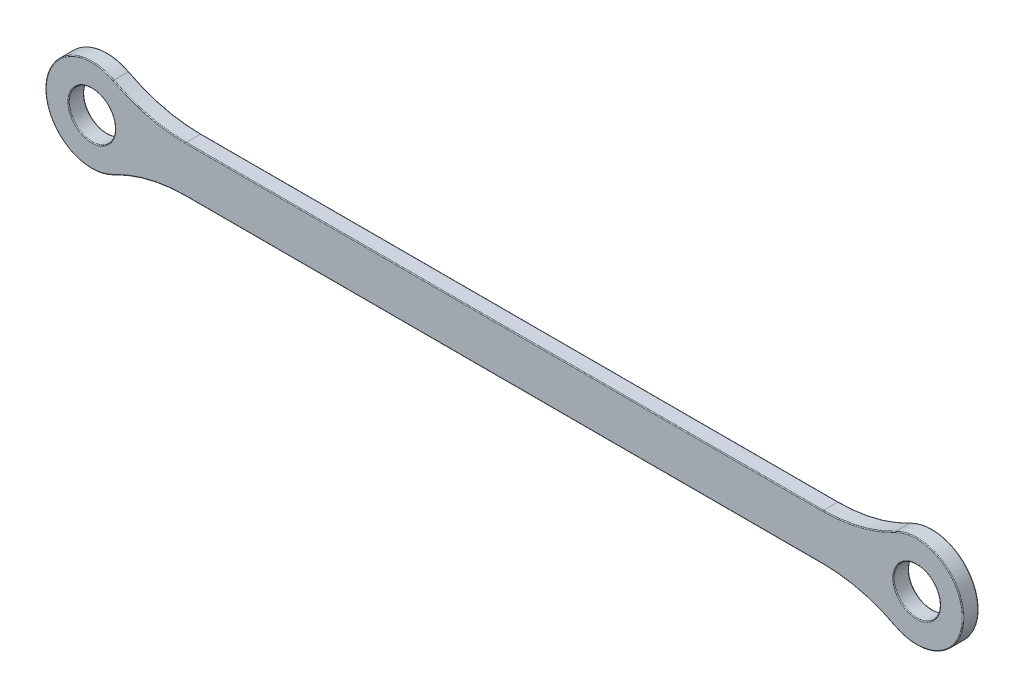
SolidWorks part; units mm, degrees
material "Plain Carbon Steel"
ref_plane "Front Plane" through (0, 0, 0) normal (0, 0, 1) x (1, 0, 0)
ref_plane "Top Plane" through (0, 0, 0) normal (0, 1, 0) x (1, 0, 0)
ref_plane "Right Plane" through (0, 0, 0) normal (1, 0, 0) x (0, 0, -1)
sketch "Sketch1" plane through (0, 0, 0) normal (0, 0, 1) x (1, 0, 0)
  line L0 (-16.6441, 156.8502) -> (-176.6441, 156.8502) construction
  line L1 (-16.6441, 156.8502) -> (-176.6441, 156.8502) construction
  line L2 (-16.6441, 156.8502) -> (-176.6441, 156.8502) construction
  line L3 (-16.6441, 152.3502) -> (-176.6441, 152.3502)
  line L4 (-16.6441, 161.3502) -> (-176.6441, 161.3502)
  arc A0 (-16.6441, 152.3502) -> (-16.6441, 161.3502) centre (-16.6441, 156.8502) ccw
  arc A1 (-176.6441, 161.3502) -> (-176.6441, 152.3502) centre (-176.6441, 156.8502) ccw
  circle A2 centre (-176.6441, 156.8502) radius 9
  circle A3 centre (-16.6441, 156.8502) radius 9
  arc A4 (-176.6441, 161.3502) -> (-176.6441, 152.3502) centre (-176.6441, 156.8502) cw
  arc A5 (-16.6441, 161.3502) -> (-16.6441, 152.3502) centre (-16.6441, 156.8502) ccw
  point P3 (-96.6441, 156.8502)
  dimension "D2" = 18
  dimension "D1" = 9
extrude "Boss-Extrude1" add sketch "Sketch1" along normal blind 3 contours A3 L4 A2 L3 | L4 A2 L3 A1 | L3 A3 L4 A0 | A5 L4 A3 L3 | L4 A4 L3 A2
fillet "Fillet1" radius 30 4 edges at (-24.4384, 161.3502, 1.5) (-24.4384, 152.3502, 1.5) (-168.8499, 152.3502, 1.5) (-168.8499, 161.3502, 1.5)
fillet "Fillet2" radius 0.15 20 edges at (-12.1441, 156.8502, 3) (-12.1441, 156.8502, 0) (-172.1441, 156.8502, 3) (-172.1441, 156.8502, 0) (-165.6634, 151.472, 3) (-165.6634, 151.472, 0) (-185.6441, 156.8502, 0) (-185.6441, 156.8502, 3) (-165.6634, 162.2284, 3) (-165.6634, 162.2284, 0) (-96.6441, 161.3502, 3) (-96.6441, 161.3502, 0) (-27.6249, 162.2284, 3) (-27.6249, 162.2284, 0) (-7.6441, 156.8502, 0) (-7.6441, 156.8502, 3) (-27.6249, 151.472, 3) (-27.6249, 151.472, 0) (-96.6441, 152.3502, 0) (-96.6441, 152.3502, 3)
